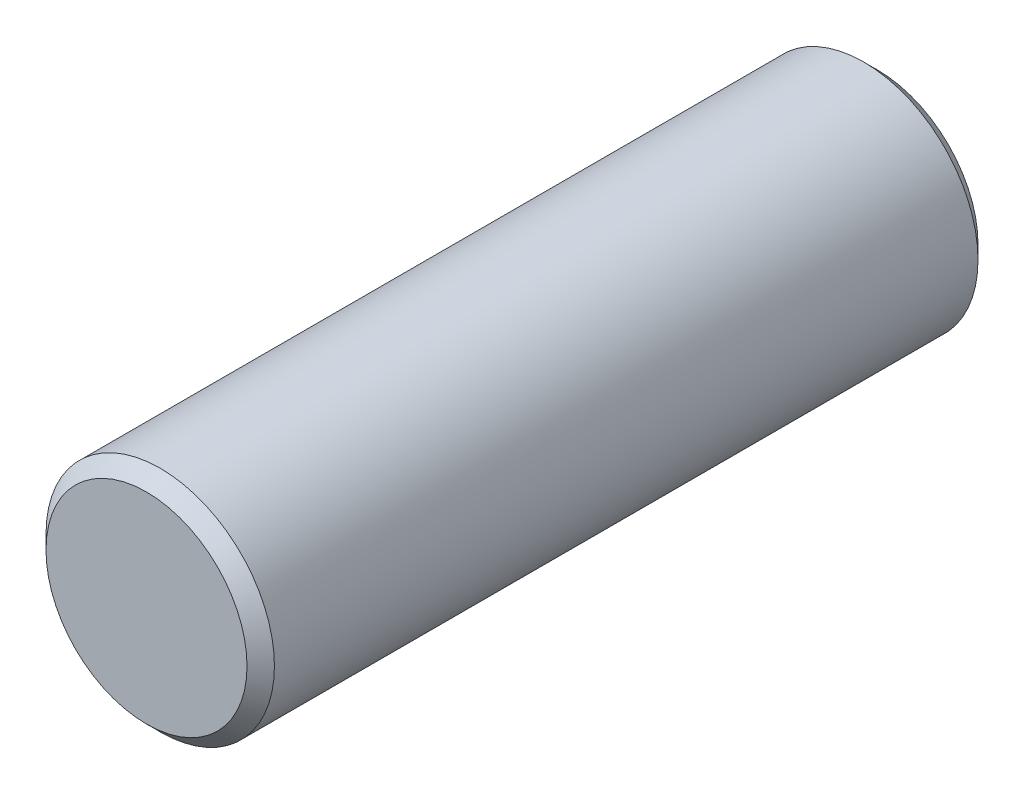
SolidWorks part; units mm, degrees
ref_plane "Front Plane" through (0, 0, 0) normal (0, 0, 1) x (1, 0, 0)
ref_plane "Top Plane" through (0, 0, 0) normal (0, 1, 0) x (1, 0, 0)
ref_plane "Right Plane" through (0, 0, 0) normal (1, 0, 0) x (0, 0, -1)
sketch "Sketch1" plane through (0, 0, 0) normal (0, 0, 1) x (1, 0, 0)
  circle A0 centre (0, 0) radius 2.5
  dimension "D1" = 5
extrude "Boss-Extrude1" add sketch "Sketch1" against normal blind 16
chamfer "Chamfer1" distance 0.3 angle 45 2 edges at (2.5, 0, -16) (2.5, 0, 0)
